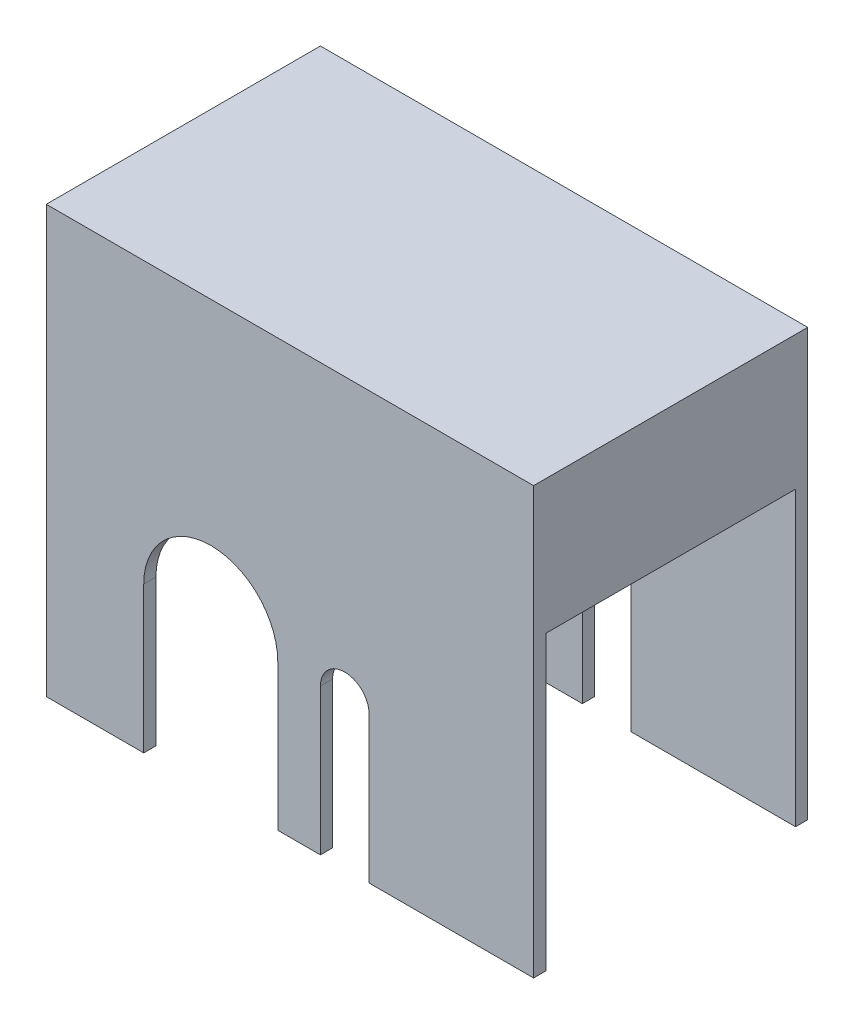
SolidWorks part; units mm, degrees
ref_plane "前视基准面" through (0, 0, 0) normal (0, 0, 1) x (1, 0, 0)
ref_plane "上视基准面" through (0, 0, 0) normal (0, 1, 0) x (1, 0, 0)
ref_plane "右视基准面" through (0, 0, 0) normal (1, 0, 0) x (0, 0, -1)
sketch "草图2" plane through (0, 0, 0) normal (0, 1, 0) x (1, 0, 0)
  line L0 (-43.9903, 20.0313) -> (-3.9903, 20.0313)
  line L1 (-3.9903, 20.0313) -> (-3.9903, -2.4687)
  line L2 (-3.9903, -2.4687) -> (-43.9903, -2.4687)
  line L3 (-43.9903, -2.4687) -> (-43.9903, 20.0313)
extrude "凸台-拉伸2" add sketch "草图2" along normal blind 25
shell "抽壳3" thickness 1
sketch "草图4" plane through (0, 0, 2.4687) normal (0, 0, 1) x (1, 0, 0)
  line L0 (-43.9903, 25) -> (-3.9903, 25) construction
  line L1 (-24.9903, 12) -> (-24.9903, 0)
  line L2 (-35.9903, 12) -> (-35.9903, 0)
  line L3 (-43.9903, 25) -> (-43.9903, 0) construction
  line L5 (-21.4903, 12) -> (-21.4903, 0)
  line L6 (13.2, 0) -> (-13.2, 0) construction
  line L7 (-17.4903, 12) -> (-17.4903, 0)
  line L8 (-21.4903, 0) -> (-17.4903, 0)
  line L9 (-24.9903, 0) -> (-35.9903, 0)
  arc A0 (-24.9903, 12) -> (-35.9903, 12) centre (-30.4903, 12) ccw
  arc A1 (-17.4903, 12) -> (-21.4903, 12) centre (-19.4903, 12) ccw
  dimension "D1" = 13
  dimension "D3" = 11
  dimension "D2" = 8
extrude "切除-拉伸2" cut sketch "草图4" against normal blind 1 and the other way through all
sketch "草图5" plane through (0, 0, -20.0313) normal (0, 0, -1) x (-1, 0, 0)
  line L0 (35.9903, 12) -> (35.9903, 0)
  line L1 (13.2, 0) -> (-13.2, 0) construction
  line L3 (3.9903, 25) -> (43.9903, 25) construction
  line L4 (17.4903, 12) -> (17.4903, 0)
  line L5 (24.9903, 0) -> (24.9903, 12)
  line L6 (21.4903, 12) -> (21.4903, 0)
  line L7 (17.4903, 0) -> (21.4903, 0)
  line L8 (24.9903, 0) -> (35.9903, 0)
  arc A0 (35.9903, 12) -> (24.9903, 12) centre (30.4903, 12) ccw
  arc A1 (21.4903, 12) -> (17.4903, 12) centre (19.4903, 12) ccw
  dimension "D1" = 3.5
  dimension "D2" = 13
extrude "切除-拉伸10" cut sketch "草图5" against normal blind 1 and the other way through all
sketch "草图6" plane through (0, 25, 0) normal (0, 1, 0) x (1, 0, 0)
  line L0 (-3.9903, 20.0313) -> (-43.9903, 20.0313)
  line L1 (-3.9903, 20.0313) -> (-43.9903, 20.0313) construction
  line L2 (-3.9903, -2.4687) -> (-3.9903, 20.0313) construction
  line L3 (-43.9903, 20.0313) -> (-43.9903, -2.4687)
  line L4 (-43.9903, -2.4687) -> (-3.9903, -2.4687)
  line L5 (-3.9903, -2.4687) -> (-3.9903, 20.0313)
extrude "凸台-拉伸3" add sketch "草图6" along normal blind 10
